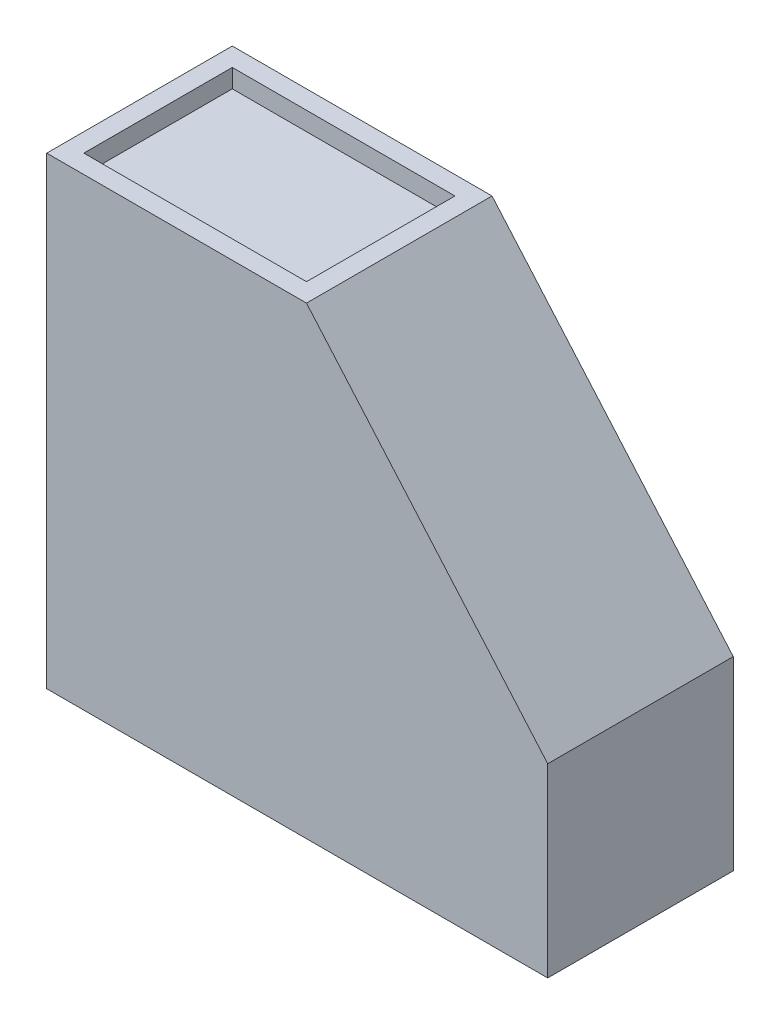
SolidWorks part; units mm, degrees
material "Acrylic (Medium-high impact)"
ref_plane "Front Plane" through (0, 0, 0) normal (0, 0, 1) x (1, 0, 0)
ref_plane "Top Plane" through (0, 0, 0) normal (0, 1, 0) x (1, 0, 0)
ref_plane "Right Plane" through (0, 0, 0) normal (1, 0, 0) x (0, 0, -1)
sketch "Sketch1" plane through (0, 0, 0) normal (0, 0, 1) x (1, 0, 0)
  line L0 (135, -25) -> (5, 125)
  line L1 (-135, -125) -> (135, -125)
  line L2 (-135, -125) -> (-135, 125)
  line L3 (-135, 125) -> (5, 125)
  line L4 (135, -125) -> (135, -25)
  line L5 (-135, -125) -> (135, 125) construction
  line L6 (-135, 125) -> (135, -125) construction
  point P0 (0, 0)
  dimension "D1" = 270
  dimension "D2" = 250
  dimension "D3" = 100
  dimension "D4" = 140
extrude "Boss-Extrude1" add sketch "Sketch1" along normal blind 100
sketch "Sketch2" plane through (0, 125, 0) normal (0, 1, 0) x (1, 0, 0)
  line L0 (-135, -100) -> (-135, 0) construction
  line L1 (-125, -90) -> (-5, -90)
  line L2 (-125, -90) -> (-125, -10)
  line L3 (-125, -10) -> (-5, -10)
  line L4 (-5, -90) -> (-5, -10)
  line L5 (-125, -90) -> (-5, -10) construction
  line L6 (-125, -10) -> (-5, -90) construction
  line L7 (5, -100) -> (-135, -100) construction
  point P0 (-65, -50)
  dimension "D1" = 120
  dimension "D2" = 80
  dimension "D3" = 10
  dimension "D4" = 10
extrude "Cut-Extrude1" cut sketch "Sketch2" against normal blind 10
